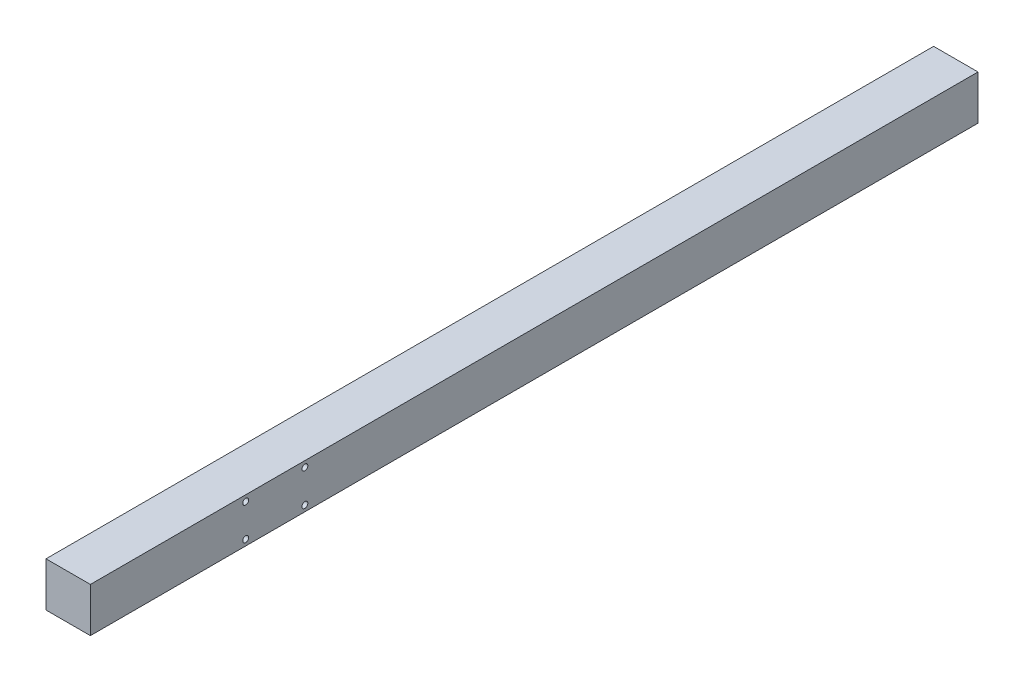
SolidWorks part; units mm, degrees
ref_plane "Front Plane" through (0, 0, 0) normal (0, 0, 1) x (1, 0, 0)
ref_plane "Top Plane" through (0, 0, 0) normal (0, 1, 0) x (1, 0, 0)
ref_plane "Right Plane" through (0, 0, 0) normal (1, 0, 0) x (0, 0, -1)
sketch "Sketch1" plane through (0, 0, 0) normal (0, 0, 1) x (1, 0, 0)
  line L1 (-15, 15) -> (15, 15)
  line L2 (-15, 15) -> (-15, -15)
  line L3 (-15, -15) -> (15, -15)
  line L4 (15, 15) -> (15, -15)
  line L5 (-15, 15) -> (15, -15) construction
  line L6 (-15, -15) -> (15, 15) construction
  point P0 (0, 0)
  dimension "D1" = 30
  dimension "D2" = 30
extrude "Boss-Extrude1" add sketch "Sketch1" along normal blind 600
sketch "Sketch5" plane through (-15, 0, 0) normal (-1, 0, 0) x (0, 0, 1)
  line L0 (600, 15) -> (0, 15) construction
  line L1 (30, 12.5) -> (5, 12.5)
  line L2 (30, 12.5) -> (30, -12.5)
  line L3 (30, -12.5) -> (5, -12.5)
  line L4 (5, 12.5) -> (5, -12.5)
  line L5 (30, 12.5) -> (5, -12.5) construction
  line L6 (30, -12.5) -> (5, 12.5) construction
  line L7 (0, 15) -> (0, -15) construction
  point P0 (17.5, 0)
  dimension "D1" = 25
  dimension "D2" = 25
  dimension "D3" = 2.5
  dimension "D4" = 5
sketch "Sketch8" plane through (0, 0, 0) normal (0, 0, -1) x (-1, 0, 0)
  line L0 (-15, -15) -> (-15, 15) construction
  line L1 (-15, 15) -> (15, 15) construction
  line L2 (15, 12.5) -> (15, -12.5) construction
  line L3 (15, -12.5) -> (15, 12.5) construction
  line L4 (15, -15) -> (-15, -15) construction
  circle A0 centre (-10, 10) radius 2.5
  circle A1 centre (10, 10) radius 2.5
  circle A2 centre (10, -10) radius 2.5
  circle A3 centre (-10, -10) radius 2.5
  dimension "D1" = 5
  dimension "D2" = 5
  dimension "D3" = 5
  dimension "D4" = 5
  dimension "D5" = 5
  dimension "D8" = 5
  dimension "D9" = 5
  dimension "D10" = 5
  dimension "D11" = 5
  dimension "D6" = 5
  dimension "D7" = 5
  dimension "D12" = 5
extrude "Cut-Extrude7" cut sketch "Sketch8" against normal blind 30
hole_wizard "Ø4.0mm Dowel Hole1" positions "3DSketch4" profile "Sketch12" hole size "Ø4.0" standard "ANSI Metric"
sketch3d "3DSketch4"
  line L0 (15, -15, 600) -> (15, -15, 0) construction
  line L1 (-15, 15, 0) -> (-15, -15, 0) construction
  line L2 (-15, 15, 600) -> (-15, 15, 0) construction
  line L3 (-15, -15, 600) -> (-15, -15, 0) construction
  point P0 (-15, 11, 495)
  point P2 (-15, 11, 455)
  point P4 (-15, -11, 455)
  point P6 (-15, -11, 495)
  point P9 (-15, 11, 495)
  point P11 (15, -15, 145.0843)
  point P16 (0, 0, 0)
  point P17 (0, 0, 0)
  point P20 (0, 0, 0)
  point P21 (0, 0, 0)
  point P22 (0, 0, 0)
  point P23 (0, 0, 0)
  dimension "D1" = 495
  dimension "D2" = 495
  dimension "D3" = 455
  dimension "D4" = 455
  dimension "D5" = 4
  dimension "D6" = 4
  dimension "D7" = 4
  dimension "D8" = 4
sketch "Sketch12" plane through (-15, 11, 495) normal (0, 1, 0) x (0, 0, 1)
  line L0 (0, 0) -> (0, 30)
  line L1 (0, 30) -> (2, 30)
  line L2 (2, 30) -> (2, 0)
  line L5 (2, 0) -> (0, 0)
  line L11 (0, -6.35) -> (0, 107.95) construction
  dimension "Thru Hole Dia." = 4
  dimension "Thru Hole Depth" = 30
